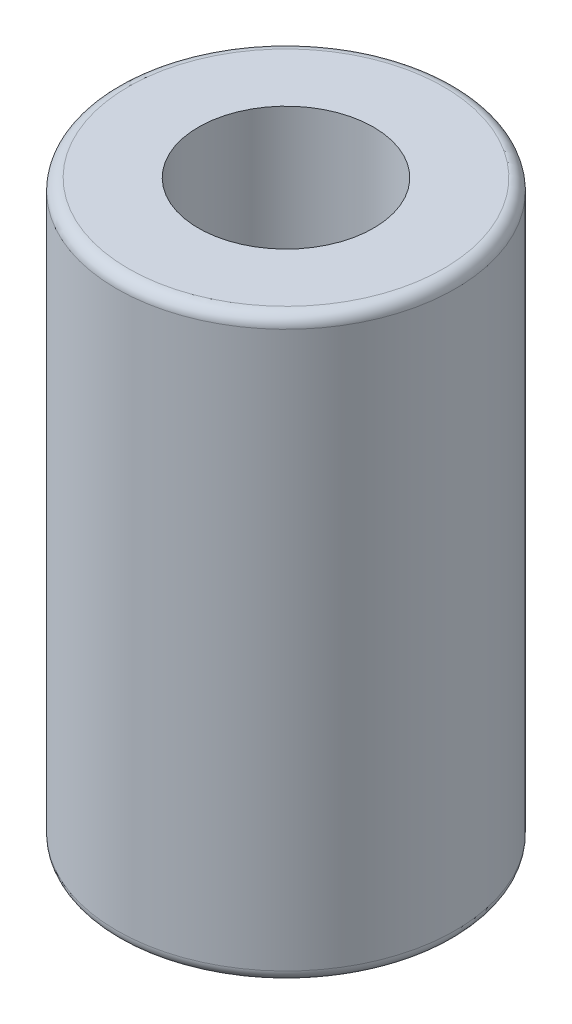
SolidWorks part; units mm, degrees
material "PS HI"
ref_plane "Front Plane" through (0, 0, 0) normal (0, 0, 1) x (1, 0, 0)
ref_plane "Top Plane" through (0, 0, 0) normal (0, 1, 0) x (1, 0, 0)
ref_plane "Right Plane" through (0, 0, 0) normal (1, 0, 0) x (0, 0, -1)
sketch "Sketch1" plane through (0, 0, 0) normal (0, 1, 0) x (1, 0, 0)
  circle A0 centre (0, 0) radius 7.25
  circle A1 centre (0, 0) radius 3.75
extrude "Boss-Extrude1" add sketch "Sketch1" along normal blind 24.8
fillet "Fillet1" radius 0.5 2 edges at (0, 0, 7.25) (0, 24.8, 7.25)
